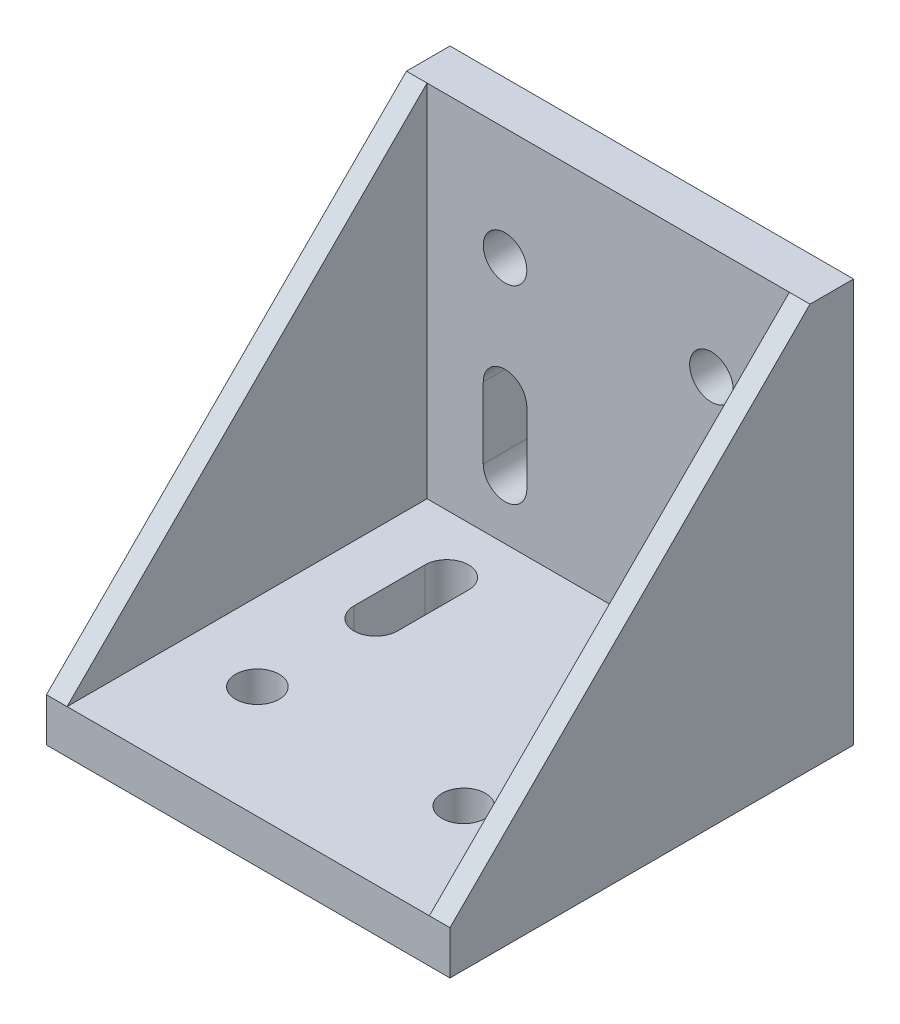
SolidWorks part; units mm, degrees
ref_plane "前视基准面" through (0, 0, 0) normal (0, 0, 1) x (1, 0, 0)
ref_plane "上视基准面" through (0, 0, 0) normal (0, 1, 0) x (1, 0, 0)
ref_plane "右视基准面" through (0, 0, 0) normal (1, 0, 0) x (0, 0, -1)
sketch "草图1" plane through (0, 0, 0) normal (0, 0, 1) x (1, 0, 0)
  line L1 (-44, 44) -> (44, 44)
  line L2 (-44, 44) -> (-44, -44)
  line L3 (-44, -44) -> (44, -44)
  line L4 (44, 44) -> (44, -44)
  line L5 (-44, 44) -> (44, -44) construction
  line L6 (-44, -44) -> (44, 44) construction
  point P0 (0, 0)
  dimension "D1" = 88
  dimension "D2" = 88
extrude "凸台-拉伸1" add sketch "草图1" along normal blind 9.5
sketch "草图2" plane through (0, 0, 0) normal (0, 0, -1) x (-1, 0, 0)
  line L0 (44, 44) -> (44, -44) construction
  line L1 (-44, -44) -> (44, -44)
  line L2 (-44, -44) -> (-44, -34.5)
  line L3 (-44, -34.5) -> (44, -34.5)
  line L4 (44, -44) -> (44, -34.5)
  dimension "D1" = 9.5
extrude "凸台-拉伸2" add sketch "草图2" against normal blind 88
sketch "草图3" plane through (-44, 0, 0) normal (-1, 0, 0) x (0, 0, 1)
  line L0 (9.5, 44) -> (88, -34.5)
  line L5 (88, -34.5) -> (9.5, -34.5)
  line L6 (9.5, -34.5) -> (9.5, 44)
extrude "凸台-拉伸3" add sketch "草图3" against normal blind 4.5
mirror "镜向1" about plane through (0, 0, 0) normal (1, 0, 0) of "凸台-拉伸3"
ref_plane "基准面1" through (0, -22, 22) normal (0, -0.7071, 0.7071) x (1, 0, 0)
sketch "草图4" plane through (0, -34.5, 0) normal (0, 1, 0) x (1, 0, 0)
  line L0 (0, -88) -> (0, -16.0975) construction
  line L1 (-39.5, -88) -> (39.5, -88) construction
  line L2 (22.5, -37.7) -> (22.5, -22.2) construction
  line L3 (17.75, -37.7) -> (17.75, -22.2)
  line L4 (27.25, -37.7) -> (27.25, -22.2)
  line L5 (-22.5, -37.7) -> (-22.5, -22.2) construction
  line L6 (-17.75, -37.7) -> (-17.75, -22.2)
  line L7 (-27.25, -37.7) -> (-27.25, -22.2)
  circle A0 centre (22.5, -63.5) radius 4.75
  arc A1 (17.75, -37.7) -> (27.25, -37.7) centre (22.5, -37.7) ccw
  arc A2 (27.25, -22.2) -> (17.75, -22.2) centre (22.5, -22.2) ccw
  arc A3 (-17.75, -37.7) -> (-27.25, -37.7) centre (-22.5, -37.7) cw
  arc A4 (-27.25, -22.2) -> (-17.75, -22.2) centre (-22.5, -22.2) cw
  circle A5 centre (-22.5, -63.5) radius 4.75
  point P9 (22.5, -29.95)
  point P16 (-22.5, -29.95)
  dimension "D1" = 22.5
  dimension "D2" = 24.5
  dimension "D4" = 25.8
  dimension "D3" = 9.5
  dimension "D5" = 15.5
extrude "切除-拉伸1" cut sketch "草图4" against normal through all
mirror "镜向2" about plane through (0, -22, 22) normal (0, -0.7071, 0.7071) of "切除-拉伸1"
